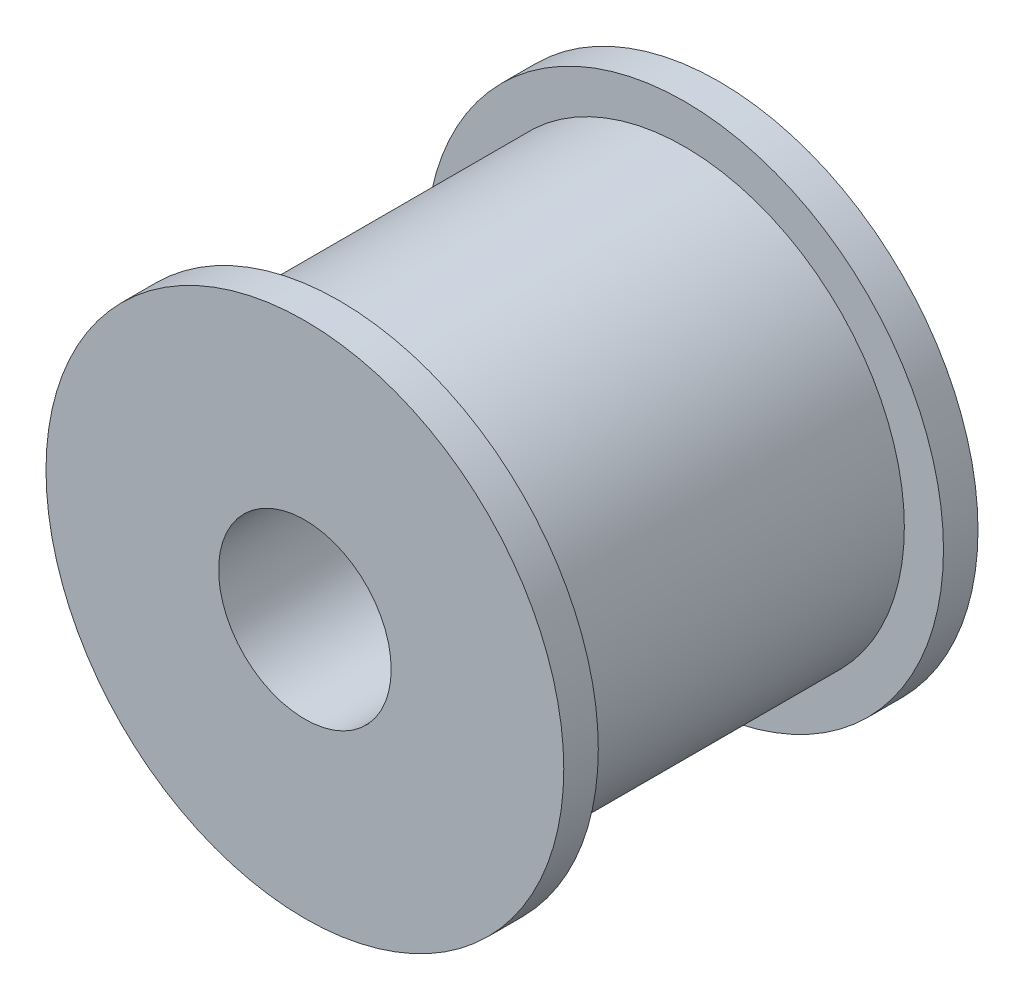
SolidWorks part; units mm, degrees
ref_plane "Front Plane" through (0, 0, 0) normal (0, 0, 1) x (1, 0, 0)
ref_plane "Top Plane" through (0, 0, 0) normal (0, 1, 0) x (1, 0, 0)
ref_plane "Right Plane" through (0, 0, 0) normal (1, 0, 0) x (0, 0, -1)
sketch "Sketch1" plane through (0, 0, 0) normal (0, 0, 1) x (1, 0, 0)
  circle A0 centre (0, 0) radius 7.5
  dimension "D1" = 15
extrude "Boss-Extrude1" add sketch "Sketch1" along normal mid plane 12
sketch "Sketch2" plane through (0, 0, 0) normal (0, 0, 1) x (1, 0, 0)
  circle A0 centre (0, 0) radius 6.3664
  circle A1 centre (0, 0) radius 7.5
  dimension "D1" = 12.7328
extrude "Cut-Extrude1" cut sketch "Sketch2" against normal mid plane 10
sketch "Sketch3" plane through (0, 0, 0) normal (0, 0, 1) x (1, 0, 0)
  circle A0 centre (0, 0) radius 2.5
  dimension "D1" = 5
extrude "Cut-Extrude2" cut sketch "Sketch3" against normal mid plane 12
